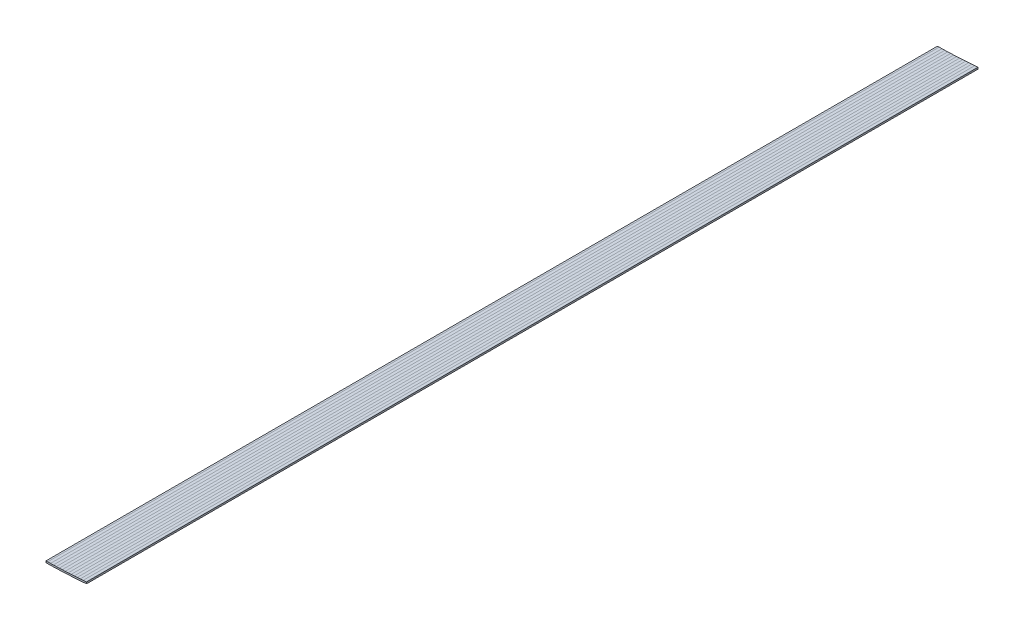
SolidWorks part; units mm, degrees
material "BLADE_CFRP_1550_PROVISIONAL"
ref_plane "Front Plane" through (0, 0, 0) normal (0, 0, 1) x (1, 0, 0)
ref_plane "Top Plane" through (0, 0, 0) normal (0, 1, 0) x (1, 0, 0)
ref_plane "Right Plane" through (0, 0, 0) normal (1, 0, 0) x (0, 0, -1)
sketch "Sketch1" plane through (0, 0, 0) normal (0, 0, 1) x (1, 0, 0)
  line L0 (21.9527, -1.5513) -> (21.2145, -1.6079)
  line L1 (21.2145, -1.6079) -> (20.473, -1.6621)
  line L2 (20.473, -1.6621) -> (19.7292, -1.7136)
  line L3 (19.7292, -1.7136) -> (18.9843, -1.7622)
  line L4 (18.9843, -1.7622) -> (18.2394, -1.8076)
  line L5 (18.2394, -1.8076) -> (17.4958, -1.8495)
  line L6 (17.4958, -1.8495) -> (16.7546, -1.8877)
  line L7 (16.7546, -1.8877) -> (16.0169, -1.9219)
  line L8 (16.0169, -1.9219) -> (15.2838, -1.9518)
  line L9 (15.2838, -1.9518) -> (14.5566, -1.9773)
  line L10 (14.5566, -1.9773) -> (13.8363, -1.998)
  line L11 (13.8363, -1.998) -> (13.124, -2.0139)
  line L12 (13.124, -2.0139) -> (12.4209, -2.0246)
  line L13 (12.4209, -2.0246) -> (12, -2.0279)
  line L14 (12, -2.0279) -> (12, -1.6279)
  line L15 (12, -1.6279) -> (12.4163, -1.6246)
  line L16 (12.4163, -1.6246) -> (13.1165, -1.6139)
  line L17 (13.1165, -1.6139) -> (13.826, -1.5982)
  line L18 (13.826, -1.5982) -> (14.5438, -1.5775)
  line L19 (14.5438, -1.5775) -> (15.2686, -1.5521)
  line L20 (15.2686, -1.5521) -> (15.9994, -1.5222)
  line L21 (15.9994, -1.5222) -> (16.735, -1.4882)
  line L22 (16.735, -1.4882) -> (17.4743, -1.4501)
  line L23 (17.4743, -1.4501) -> (18.216, -1.4083)
  line L24 (18.216, -1.4083) -> (18.9591, -1.363)
  line L25 (18.9591, -1.363) -> (19.7023, -1.3145)
  line L26 (19.7023, -1.3145) -> (20.4446, -1.2631)
  line L27 (20.4446, -1.2631) -> (21.1847, -1.209)
  line L28 (21.1847, -1.209) -> (21.9215, -1.1525)
  line L29 (21.9215, -1.1525) -> (22, -1.1462)
  line L30 (22, -1.1462) -> (22, -1.5475)
  line L31 (22, -1.5475) -> (21.9527, -1.5513)
extrude "Defined_Material_Section_L220" add sketch "Sketch1" along normal blind 220
